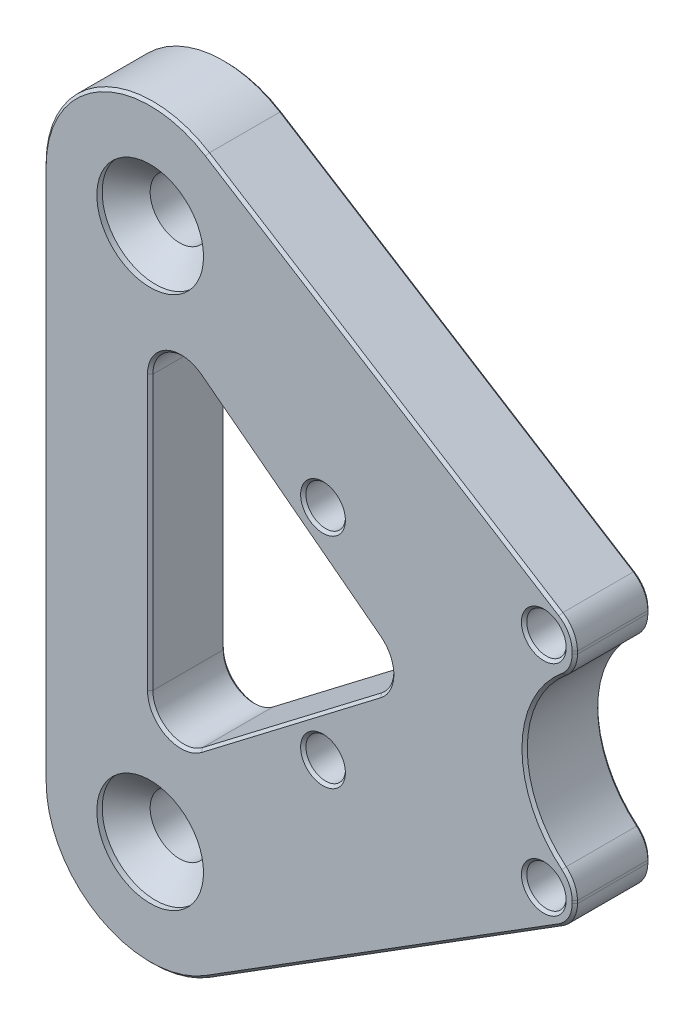
SolidWorks part; units mm, degrees
ref_plane "Front Plane" through (0, 0, 0) normal (0, 0, 1) x (1, 0, 0)
ref_plane "Top Plane" through (0, 0, 0) normal (0, 1, 0) x (1, 0, 0)
ref_plane "Right Plane" through (0, 0, 0) normal (1, 0, 0) x (0, 0, -1)
sketch "Sketch1" plane through (0, 0, 1.1) normal (0, 0, 1) x (1, 0, 0)
  line L0 (-27.3895, 33.4731) -> (5.7397, 12.7072)
  line L1 (-22.7005, 26.5365) -> (-22.7005, -11.673) construction
  line L2 (-27.3895, -33.4731) -> (5.7397, -12.7072)
  line L3 (7.0995, 10.25) -> (7.0995, 8.5352)
  line L4 (-42.7005, 13.15) -> (-42.7005, -8.8269) construction
  line L5 (-22.7005, 0) -> (-42.7005, 0) construction
  line L6 (-32.7005, 21.0577) -> (-32.7005, -15.7288) construction
  line L7 (-30.8798, 0) -> (28.9169, 0) construction
  line L8 (-42.7005, 25) -> (-42.7005, -25)
  line L9 (7.0995, -8.5352) -> (7.0995, -10.25)
  circle A0 centre (-16.5005, -10.25) radius 1.25
  circle A1 centre (4.1995, 10.25) radius 1.25
  circle A2 centre (4.1995, -10.25) radius 1.25
  circle A4 centre (-16.5005, 10.25) radius 1.25
  circle A5 centre (-16.5005, -10.25) radius 2.9 construction
  arc A6 (5.7397, -12.7072) -> (7.0995, -10.25) centre (4.1995, -10.25) ccw
  circle A7 centre (-16.5005, 10.25) radius 2.9 construction
  arc A8 (7.0995, 10.25) -> (5.7397, 12.7072) centre (4.1995, 10.25) ccw
  circle A9 centre (-32.7005, 25) radius 2.75
  arc A10 (-27.3895, 33.4731) -> (-42.7005, 25) centre (-32.7005, 25) ccw
  circle A12 centre (12.4995, 0) radius 10.1
  circle A13 centre (12.4995, 0) radius 10.1
  circle A15 centre (-32.7005, -25) radius 2.75
  arc A16 (-27.3895, -33.4731) -> (-42.7005, -25) centre (-32.7005, -25) cw
  point P31 (-32.7005, 0)
  dimension "D1" = 2.5
  dimension "D2" = 5.8
  dimension "D7" = 50
  dimension "D6" = 5.5
  dimension "D3" = 35.2
  dimension "D4" = 0.5
  dimension "D5" = 20
extrude "Boss-Extrude1" add sketch "Sketch1" along normal blind 7.1
sketch "Sketch2" plane through (0, 0, 8.2) normal (0, 0, 1) x (1, 0, 0)
  circle A0 centre (-16.5005, 10.25) radius 1.85
  circle A1 centre (4.1995, 10.25) radius 1.85
  circle A2 centre (-16.5005, -10.25) radius 1.85
  circle A3 centre (4.1995, -10.25) radius 1.85
  dimension "D1" = 3.7
extrude "Cut-Extrude1" cut sketch "Sketch2" against normal offset from surface (5.6 mm away) 1.5 up to face at (-10.9363, 0, 1.1)
fillet "Fillet1" radius 2.9 2 edges at (7.0995, -8.5352, 4.65) (7.0995, 8.5352, 4.65)
hole_wizard "CSK for M5 Flat Head Machine Screw1" positions "Sketch3" profile "Sketch4" countersink size "M5" standard "ANSI Metric" end condition through all
sketch "Sketch3" plane through (0, 0, 8.2) normal (0, 0, 1) x (1, 0, 0)
  point P0 (-32.7005, 25)
  point P3 (-32.7005, -25)
sketch "Sketch4" plane through (-32.7005, 25, 8.2) normal (1, 0, 0) x (0, -1, 0)
  line L0 (0, 0) -> (0, 7.1)
  line L1 (0, 7.1) -> (2.75, 7.1)
  line L2 (2.75, 7.1) -> (2.75, 2.75)
  line L3 (2.75, 2.75) -> (5, 0.5)
  line L4 (5, 0.5) -> (5, 0)
  line L6 (5, 0) -> (0, 0)
  line L7 (-2.75, 2.75) -> (-5, 0.5) construction
  line L11 (0, -6.35) -> (0, 107.95) construction
  dimension "Thru Hole Dia." = 5.5
  dimension "Thru Hole Depth" = 7.1
  dimension "C'Sink Dia." = 10
  dimension "C'Sink Angle" = 90
  dimension "Head Clearance" = 0.5
sketch "Sketch5" plane through (0, 0, 8.2) normal (0, 0, 1) x (1, 0, 0)
  line L0 (-32.7005, 25) -> (-32.7005, -25)
  line L1 (-32.7005, -25) -> (0, 0) construction
  line L2 (0, 0) -> (-32.7005, 25) construction
  line L3 (-3.0368, -3.9722) -> (-35.7373, 21.0278)
  line L4 (-58.5824, 0) -> (16.7402, 0) construction
  line L5 (-3.0368, 3.9722) -> (-35.7373, -21.0278)
  dimension "D1" = 5
extrude "Cut-Extrude2" cut sketch "Sketch5" against normal up to next contours L5 L3 L0
fillet "Fillet2" radius 2.9 3 edges at (-32.7005, -18.7062, 4.65) (-8.2324, 0, 4.65) (-32.7005, 18.7062, 4.65)
chamfer "Chamfer1" distance 0.25 angle 45 50 edges at (-14.6505, -10.25, 2.6) (-14.6505, -10.25, 8.2) (6.0495, -10.25, 2.6) (6.0495, -10.25, 8.2) (6.0495, 10.25, 2.6) (6.0495, 10.25, 8.2) (-14.6505, 10.25, 2.6) (-14.6505, 10.25, 8.2) (-15.2505, -10.25, 1.1) (5.4495, -10.25, 1.1) (5.4495, 10.25, 1.1) (-15.2505, 10.25, 1.1) (-29.9505, 25, 1.1) (-29.9505, -25, 1.1) (7.0995, 10.1277, 8.2) (7.0995, 10.1277, 1.1) (6.7369, 11.6542, 1.1) (6.7369, 11.6542, 8.2) (6.8243, 8.7725, 8.2) (6.8243, 8.7725, 1.1) (-10.8249, 23.0901, 1.1) (-10.8249, 23.0901, 8.2) (2.3995, 0, 8.2) (2.3995, 0, 1.1) (-37.5425, 33.7496, 1.1) (-37.5425, 33.7496, 8.2) (6.8243, -8.7725, 8.2) (6.8243, -8.7725, 1.1) (-42.7005, 0, 1.1) (-42.7005, 0, 8.2) (7.0995, -10.1277, 1.1) (7.0995, -10.1277, 8.2) (-37.5425, -33.7496, 1.1) (-37.5425, -33.7496, 8.2) (6.7369, -11.6542, 1.1) (6.7369, -11.6542, 8.2) (-10.8249, -23.0901, 1.1) (-10.8249, -23.0901, 8.2) (-10.1072, 0, 1.1) (-10.1072, 0, 8.2) (-19.6425, 8.7232, 1.1) (-19.6425, 8.7232, 8.2) (-19.6425, -8.7232, 1.1) (-19.6425, -8.7232, 8.2) (-31.0854, 15.4385, 1.1) (-31.0854, 15.4385, 8.2) (-31.0854, -15.4385, 1.1) (-31.0854, -15.4385, 8.2) (-32.7005, 0, 8.2) (-32.7005, 0, 1.1)
